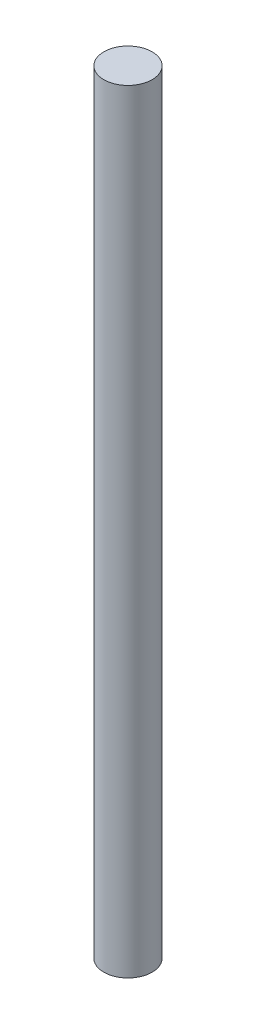
SolidWorks part; units mm, degrees
ref_plane "Front Plane" through (0, 0, 0) normal (0, 0, 1) x (1, 0, 0)
ref_plane "Top Plane" through (0, 0, 0) normal (0, 1, 0) x (1, 0, 0)
ref_plane "Right Plane" through (0, 0, 0) normal (1, 0, 0) x (0, 0, -1)
sketch "Sketch1" plane through (0, 0, 0) normal (0, 1, 0) x (1, 0, 0)
  circle A0 centre (0, 0) radius 1.5
  dimension "D1" = 3
extrude "Boss-Extrude1" add sketch "Sketch1" along normal blind 48
